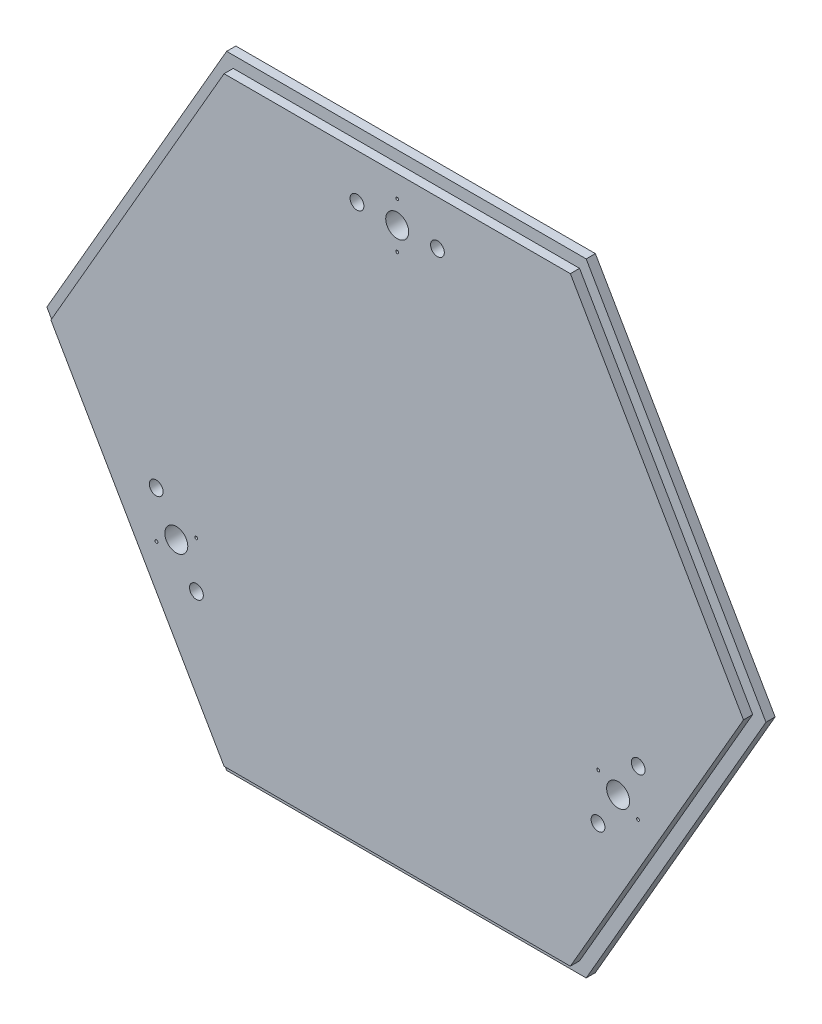
SolidWorks part; units mm, degrees
ref_plane "Front Plane" through (0, 0, 0) normal (0, 0, 1) x (1, 0, 0)
ref_plane "Top Plane" through (0, 0, 0) normal (0, 1, 0) x (1, 0, 0)
ref_plane "Right Plane" through (0, 0, 0) normal (1, 0, 0) x (0, 0, -1)
sketch "Sketch1" plane through (0, 0, 0) normal (0, 0, 1) x (1, 0, 0)
  line L1 (160.5034, 278) -> (-160.5034, 278)
  line L2 (-160.5034, 278) -> (-321.0067, 0)
  line L3 (-321.0067, 0) -> (-160.5034, -278)
  line L4 (-160.5034, -278) -> (160.5034, -278)
  line L5 (160.5034, -278) -> (321.0067, 0)
  line L6 (321.0067, 0) -> (160.5034, 278)
  circle A0 centre (0, 0) radius 278 construction
  circle A1 centre (0, 0) radius 150 construction
  dimension "D1" = 300
  dimension "D2" = 556
extrude "Boss-Extrude1" add sketch "Sketch1" along normal blind 16
sketch "Sketch3" plane through (0, 0, 16) normal (0, 0, 1) x (1, 0, 0)
  line L0 (0, 278) -> (0, 222) construction
  line L1 (321.0067, 0) -> (160.5034, 278) construction
  line L2 (160.5034, 278) -> (-160.5034, 278) construction
  line L3 (-160.5034, 278) -> (-321.0067, 0) construction
  line L4 (-321.0067, 0) -> (-160.5034, -278) construction
  line L5 (-160.5034, -278) -> (160.5034, -278) construction
  line L6 (160.5034, -278) -> (321.0067, 0) construction
  line L7 (240.7551, -139) -> (192.2576, -111) construction
  line L8 (-240.7551, -139) -> (-192.2576, -111) construction
  line L9 (-35, 222) -> (0, 222) construction
  line L10 (0, 222) -> (35, 222) construction
  line L11 (-209.7576, -80.6891) -> (-192.2576, -111) construction
  line L12 (-192.2576, -111) -> (-174.7576, -141.3109) construction
  line L13 (174.7576, -141.3109) -> (192.2576, -111) construction
  line L14 (192.2576, -111) -> (209.7576, -80.6891) construction
  circle A0 centre (0, 0) radius 278 construction
  circle A1 centre (35, 222) radius 6
  circle A2 centre (-35, 222) radius 6
  circle A3 centre (-209.7576, -80.6891) radius 6
  circle A4 centre (-174.7576, -141.3109) radius 6
  circle A5 centre (174.7576, -141.3109) radius 6
  circle A6 centre (209.7576, -80.6891) radius 6
  dimension "D1" = 556
  dimension "D4" = 12
  dimension "D2" = 56
  dimension "D3" = 35
  dimension "D5" = 222
extrude "Cut-Extrude1" cut sketch "Sketch3" against normal up to next
sketch "Sketch4" plane through (0, 0, 16) normal (0, 0, 1) x (1, 0, 0)
  line L12 (301.3768, 0) -> (150.6884, 261)
  line L13 (150.6884, 261) -> (-150.6884, 261)
  line L14 (-150.6884, 261) -> (-301.3768, 0)
  line L15 (-301.3768, 0) -> (-150.6884, -261)
  line L16 (-150.6884, -261) -> (150.6884, -261)
  line L17 (150.6884, -261) -> (301.3768, 0)
  line L18 (301.3768, 0) -> (150.6884, 261)
  line L19 (150.6884, 261) -> (-150.6884, 261)
  line L20 (-150.6884, 261) -> (-301.3768, 0)
  line L21 (-301.3768, 0) -> (-150.6884, -261)
  line L22 (-150.6884, -261) -> (150.6884, -261)
  line L23 (150.6884, -261) -> (301.3768, 0)
  dimension "D1" = 17
extrude "Cut-Extrude2" cut sketch "Sketch4" against normal blind 8 flip side to cut
sketch "Sketch5" plane through (0, 0, 16) normal (0, 0, 1) x (1, 0, 0)
  line L0 (35, 222) -> (-35, 222) construction
  line L1 (-209.7576, -80.6891) -> (-174.7576, -141.3109) construction
  line L2 (174.7576, -141.3109) -> (209.7576, -80.6891) construction
  line L3 (174.9371, -101) -> (192.2576, -111) construction
  line L6 (-174.9371, -101) -> (-192.2576, -111) construction
  line L7 (-192.2576, -111) -> (-209.5781, -121) construction
  line L14 (192.2576, -111) -> (209.5781, -121) construction
  line L21 (0, 202) -> (0, 222) construction
  line L23 (0, 222) -> (0, 242) construction
  circle A0 centre (209.5781, -121) radius 1.25
  circle A1 centre (174.9371, -101) radius 1.25
  circle A2 centre (-192.2576, -111) radius 10
  circle A3 centre (0, 222) radius 10
  circle A6 centre (-209.5781, -121) radius 1.25
  circle A7 centre (-174.9371, -101) radius 1.25
  circle A12 centre (0, 242) radius 1.25
  circle A13 centre (0, 202) radius 1.25
  circle A18 centre (192.2576, -111) radius 10
  point P10 (0, 222)
  point P13 (192.2576, -111)
  dimension "D3" = 20
  dimension "D2" = 2.5
  dimension "D5" = 20
  dimension "D8" = 2.5
  dimension "D14" = 2.5
  dimension "D19" = 40
  dimension "D13" = 40
  dimension "D9" = 40
  dimension "D4" = 20
extrude "Cut-Extrude3" cut sketch "Sketch5" against normal through all
sketch "Sketch8" plane through (0, 0, 0) normal (0, 0, -1) x (-1, 0, 0)
  line L6 (-156.4619, 271) -> (-312.9238, 0)
  line L7 (-156.4619, 271) -> (-312.9238, 0)
  line L8 (-312.9238, 0) -> (-156.4619, -271)
  line L9 (-312.9238, 0) -> (-156.4619, -271)
  line L10 (-156.4619, -271) -> (156.4619, -271)
  line L11 (-156.4619, -271) -> (156.4619, -271)
  line L12 (156.4619, -271) -> (312.9238, 0)
  line L13 (156.4619, -271) -> (312.9238, 0)
  line L14 (312.9238, 0) -> (156.4619, 271)
  line L15 (312.9238, 0) -> (156.4619, 271)
  line L16 (156.4619, 271) -> (-156.4619, 271)
  line L17 (156.4619, 271) -> (-156.4619, 271)
  line M46 (-160.5034, 278) -> (-321.0067, 0)
  line M47 (-321.0067, 0) -> (-160.5034, -278)
  line M48 (-160.5034, -278) -> (160.5034, -278)
  line M49 (160.5034, -278) -> (321.0067, 0)
  line M50 (321.0067, 0) -> (160.5034, 278)
  line M51 (160.5034, 278) -> (-160.5034, 278)
  dimension "D1" = 7
extrude "Cut-Extrude6" cut sketch "Sketch8" against normal through all contours L17 L15 L13 L11 L9 L7 M51 M46 M47 M48 M49 M50
equation "\"Build Platform Size\"= 300"
equation "\"Rod Diameter\"= 12"
equation "\"Rod Spacing\"= 70"
equation "\"Edge Rod Spacing\"= 50"
equation "\"Base Diameter\"= \"Build Platform Size\" + 2 * \"Carriage Depth\" + 2 * \"Rod Diameter\" + 2 * \"Edge Rod Spacing\" + 2 * \"Platform Radius\""
equation "\"Carriage Depth\"= 20"
equation "\"D2@Sketch1\"=\"Base Diameter\""
equation "\"D1@Sketch1\"=\"Build Platform Size\""
equation "\"D1@Sketch3\"=\"Base Diameter\""
equation "\"D2@Sketch3\"=\"Edge Rod Spacing\"+\"Rod Diameter\"/2"
equation "\"D3@Sketch3\"=\"Rod Spacing\"/2"
equation "\"D4@Sketch3\"=\"Rod Diameter\""
equation "\"Platform Radius\"= 46"
